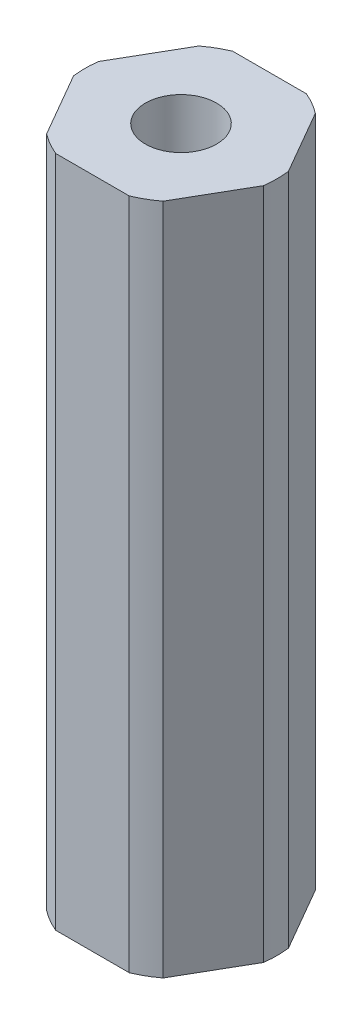
SolidWorks part; units mm, degrees
material "6061-T6 (SS)"
ref_plane "Front" through (0, 0, 0) normal (0, 0, 1) x (1, 0, 0)
ref_plane "Top" through (0, 0, 0) normal (0, 1, 0) x (1, 0, 0)
ref_plane "Right" through (0, 0, 0) normal (1, 0, 0) x (0, 0, -1)
sketch "Sketch1" plane through (0, 0, 0) normal (0, 1, 0) x (1, 0, 0)
  line L1 (3.6662, -6.35) -> (7.3323, 0)
  line L2 (7.3323, 0) -> (3.6662, 6.35)
  line L3 (3.6662, 6.35) -> (-3.6662, 6.35)
  line L4 (-3.6662, 6.35) -> (-7.3323, 0)
  line L5 (-7.3323, 0) -> (-3.6662, -6.35)
  line L6 (-3.6662, -6.35) -> (3.6662, -6.35)
  circle A0 centre (0, 0) radius 6.35 construction
  circle A1 centre (0, 0) radius 6.8758
  circle A2 centre (0, 0) radius 2.5527
  dimension "D2" = 13.7516
  dimension "D3" = 5.1054
  dimension "D1" = 12.7
extrude "Boss-Extrude1" add sketch "Sketch1" along normal mid plane 48.26 contours L6 A1 L1 L2 L3 L4 L5 A2
